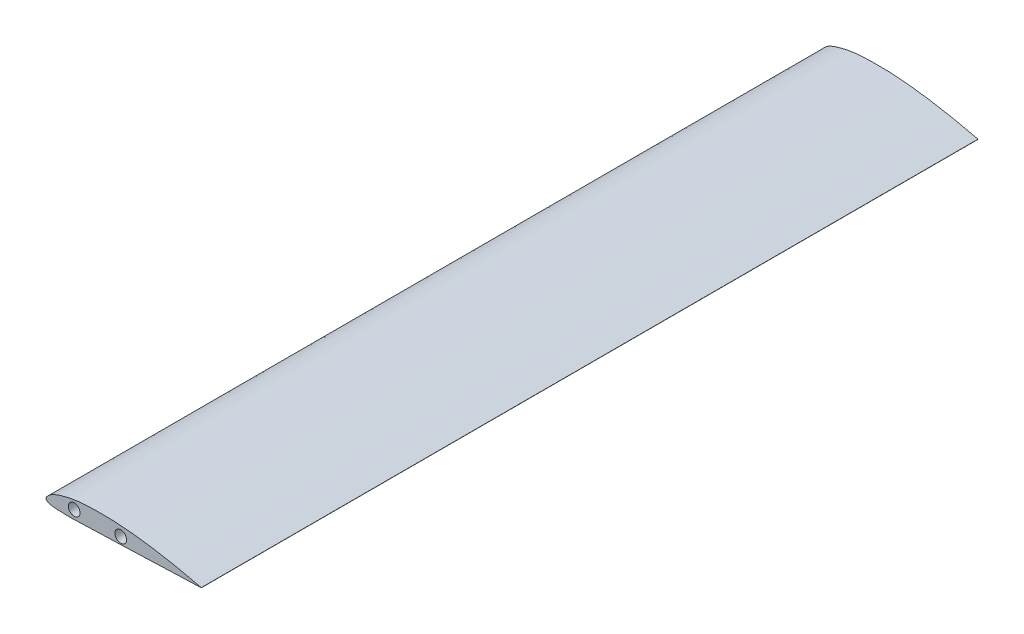
SolidWorks part; units mm, degrees
material "ABS"
ref_plane "Front Plane" through (0, 0, 0) normal (0, 0, 1) x (1, 0, 0)
ref_plane "Top Plane" through (0, 0, 0) normal (0, 1, 0) x (1, 0, 0)
ref_plane "Right Plane" through (0, 0, 0) normal (1, 0, 0) x (0, 0, -1)
curve "Curve1"
  spline degree 3 poles (25.4, 0.0152, 0) (25.3153, 0.0353, 0) (25.146, 0.0754, 0) (24.892, 0.1355, 0) (24.6381, 0.1953, 0) (24.2995, 0.2744, 0) (23.8763, 0.3719, 0) (23.3683, 0.4859, 0) (22.8603, 0.5973, 0) (22.3523, 0.7062, 0) (21.8443, 0.8125, 0) (21.3363, 0.9162, 0) (20.8283, 1.017, 0) (20.3203, 1.1151, 0) (19.8123, 1.2102, 0) (19.3043, 1.3024, 0) (18.7962, 1.3915, 0) (18.2882, 1.4777, 0) (17.7802, 1.5609, 0) (17.2722, 1.6409, 0) (16.7643, 1.7177, 0) (16.2563, 1.7908, 0) (15.7483, 1.8601, 0) (15.2403, 1.9251, 0) (14.7323, 1.9856, 0) (14.2242, 2.0416, 0) (13.7162, 2.093, 0) (13.2082, 2.1398, 0) (12.7002, 2.182, 0) (12.1922, 2.2197, 0) (11.6842, 2.2524, 0) (11.1761, 2.2798, 0) (10.6681, 2.3014, 0) (10.1601, 2.3168, 0) (9.652, 2.3257, 0) (9.144, 2.3283, 0) (8.636, 2.3252, 0) (8.128, 2.3169, 0) (7.6199, 2.3039, 0) (7.1119, 2.2871, 0) (6.6038, 2.2641, 0) (6.0956, 2.2327, 0) (5.5873, 2.1902, 0) (5.079, 2.1342, 0) (4.5707, 2.0617, 0) (4.0625, 1.9727, 0) (3.5542, 1.8677, 0) (3.0455, 1.7457, 0) (2.5366, 1.6033, 0) (2.0278, 1.436, 0) (1.6043, 1.2762, 0) (1.2667, 1.1258, 0) (1.0109, 0.9949, 0) (0.7528, 0.8393, 0) (0.5145, 0.6577, 0) (0.3356, 0.4854, 0) (0.199, 0.3469, 0) (0.1123, 0.2457, 0) (0.0552, 0.1586, 0) (0.0273, 0.1015, 0) (0.0095, 0.0523, 0) (-0.0066, -0.0188, 0) (0.0016, -0.0927, 0) (0.0273, -0.1571, 0) (0.0549, -0.2082, 0) (0.1111, -0.2828, 0) (0.1967, -0.3619, 0) (0.3302, -0.4523, 0) (0.5196, -0.5255, 0) (0.7613, -0.5742, 0) (1.0151, -0.6246, 0) (1.2693, -0.6634, 0) (1.608, -0.6993, 0) (2.0318, -0.7237, 0) (2.5398, -0.7478, 0) (3.0479, -0.7623, 0) (3.556, -0.7692, 0) (4.064, -0.7694, 0) (4.572, -0.764, 0) (5.08, -0.7541, 0) (5.588, -0.7407, 0) (6.096, -0.7247, 0) (6.604, -0.7067, 0) (7.112, -0.6877, 0) (7.62, -0.6682, 0) (8.128, -0.6491, 0) (8.636, -0.6304, 0) (9.144, -0.6118, 0) (9.652, -0.5934, 0) (10.16, -0.5749, 0) (10.668, -0.5564, 0) (11.176, -0.5378, 0) (11.684, -0.519, 0) (12.192, -0.5004, 0) (12.7, -0.4816, 0) (13.208, -0.4629, 0) (13.716, -0.4443, 0) (14.224, -0.4256, 0) (14.732, -0.407, 0) (15.24, -0.3883, 0) (15.748, -0.3697, 0) (16.256, -0.3511, 0) (16.764, -0.3324, 0) (17.272, -0.3137, 0) (17.78, -0.2951, 0) (18.288, -0.2764, 0) (18.796, -0.2578, 0) (19.304, -0.2391, 0) (19.812, -0.2205, 0) (20.32, -0.2018, 0) (20.828, -0.1831, 0) (21.336, -0.1645, 0) (21.844, -0.1458, 0) (22.352, -0.1271, 0) (22.86, -0.1085, 0) (23.368, -0.0898, 0) (23.876, -0.0712, 0) (24.2993, -0.0556, 0) (24.638, -0.0432, 0) (24.892, -0.0339, 0) (25.146, -0.0246, 0) (25.3153, -0.0183, 0) (25.4, -0.0152, 0) knots 0 0 0 0 0.005028 0.010055 0.015081 0.020105 0.030145 0.040174 0.050191 0.060198 0.070194 0.08018 0.090156 0.100121 0.110076 0.12002 0.129954 0.139879 0.149793 0.159699 0.169594 0.17948 0.189355 0.199219 0.209073 0.218917 0.228751 0.238577 0.248396 0.258207 0.268012 0.277811 0.287604 0.297393 0.307179 0.316964 0.326749 0.336535 0.346322 0.356113 0.365908 0.375711 0.385531 0.395376 0.405259 0.415192 0.425184 0.435248 0.445412 0.455711 0.466191 0.471552 0.477055 0.482787 0.488946 0.494316 0.497126 0.500187 0.502001 0.503128 0.50385 0.50502 0.507318 0.507987 0.509024 0.510668 0.513358 0.515716 0.519949 0.524973 0.529954 0.534903 0.539824 0.54963 0.559425 0.569214 0.579 0.588784 0.59857 0.608356 0.618144 0.627933 0.637724 0.647515 0.657307 0.667099 0.67689 0.686681 0.696472 0.706263 0.716054 0.725846 0.735637 0.745428 0.755219 0.765011 0.774802 0.784593 0.794384 0.804176 0.813967 0.823758 0.833549 0.84334 0.853132 0.862923 0.872714 0.882505 0.892297 0.902088 0.911879 0.92167 0.931461 0.941253 0.951044 0.960835 0.970626 0.980418 0.985313 0.990209 0.995104 1 1 1 1
sketch "Sketch1" plane through (0, 0, 0) normal (0, 0, 1) x (1, 0, 0)
  line L1 (50.8, 0.0304) -> (50.8, -0.0304)
  line L2 (0, 0) -> (50.8, -0.0304) construction
  spline S1 degree 3 poles (50.8, 0.0304) (50.6307, 0.0706) (50.292, 0.1509) (49.7841, 0.271) (49.2761, 0.3906) (48.599, 0.5489) (47.7526, 0.7437) (46.7366, 0.9719) (45.7205, 1.1946) (44.7045, 1.4124) (43.6885, 1.625) (42.6725, 1.8324) (41.6565, 2.034) (40.6405, 2.2302) (39.6245, 2.4204) (38.6085, 2.6048) (37.5925, 2.7831) (36.5765, 2.9555) (35.5605, 3.1217) (34.5445, 3.2819) (33.5285, 3.4355) (32.5125, 3.5817) (31.4966, 3.7202) (30.4805, 3.8502) (29.1265, 4.0115) (27.7717, 4.1547) (26.4164, 4.2796) (25.4004, 4.3641) (24.3843, 4.4393) (23.03, 4.5266) (21.6752, 4.5925) (20.3202, 4.6337) (19.3041, 4.6513) (18.288, 4.6566) (17.2719, 4.6503) (16.2559, 4.6338) (15.2399, 4.6078) (14.2238, 4.5741) (13.2075, 4.5283) (12.1912, 4.4655) (11.1747, 4.3804) (10.158, 4.2684) (9.1414, 4.1234) (8.125, 3.9453) (7.1083, 3.7354) (6.091, 3.4914) (5.0732, 3.2065) (4.0556, 2.872) (3.2085, 2.5523) (2.5334, 2.2517) (2.0218, 1.9898) (1.5056, 1.6786) (1.0291, 1.3154) (0.6712, 0.9708) (0.398, 0.6939) (0.2245, 0.4914) (0.1104, 0.3171) (0.0546, 0.2029) (0.019, 0.1046) (-0.0133, -0.0375) (0.0031, -0.1854) (0.0546, -0.3141) (0.1099, -0.4165) (0.2221, -0.5657) (0.3933, -0.7238) (0.6603, -0.9046) (1.0392, -1.0509) (1.5225, -1.1483) (2.0302, -1.2493) (2.5386, -1.3268) (3.216, -1.3987) (4.0636, -1.4474) (5.0796, -1.4956) (6.0958, -1.5247) (7.112, -1.5384) (8.128, -1.5388) (9.1441, -1.528) (10.4989, -1.5016) (11.8535, -1.4613) (13.208, -1.4134) (14.224, -1.3753) (15.24, -1.3363) (16.256, -1.2981) (17.272, -1.2607) (18.288, -1.2236) (19.304, -1.1868) (20.32, -1.1498) (21.336, -1.1127) (22.352, -1.0755) (23.368, -1.0381) (24.384, -1.0007) (25.4, -0.9633) (26.416, -0.9259) (27.432, -0.8885) (29.1253, -0.8264) (30.8187, -0.7642) (32.8507, -0.6897) (34.2053, -0.6398) (35.56, -0.5902) (36.576, -0.5528) (37.592, -0.5155) (38.608, -0.4782) (39.624, -0.4409) (40.64, -0.4035) (41.656, -0.3663) (42.672, -0.3289) (43.688, -0.2917) (44.704, -0.2543) (45.72, -0.217) (46.736, -0.1797) (47.752, -0.1424) (48.5987, -0.1113) (49.276, -0.0864) (49.784, -0.0678) (50.292, -0.0491) (50.6307, -0.0367) (50.8, -0.0304) knots 0 0 0 0 0.005028 0.010055 0.015081 0.020105 0.030145 0.040174 0.050191 0.060198 0.070194 0.08018 0.090156 0.100121 0.110076 0.12002 0.129954 0.139879 0.149793 0.159699 0.169594 0.17948 0.189355 0.199219 0.209073 0.228751 0.238577 0.248396 0.258207 0.268012 0.287604 0.297393 0.307179 0.316964 0.326749 0.336535 0.346322 0.356113 0.365908 0.375711 0.385531 0.395376 0.405259 0.415192 0.425184 0.435248 0.445412 0.455711 0.466191 0.471552 0.477055 0.482787 0.488946 0.494316 0.497126 0.500187 0.502001 0.503128 0.50385 0.50502 0.507318 0.507987 0.509024 0.510668 0.513358 0.515716 0.519949 0.524973 0.529954 0.534903 0.539824 0.54963 0.559425 0.569214 0.579 0.588784 0.59857 0.608356 0.627933 0.637724 0.647515 0.657307 0.667099 0.67689 0.686681 0.696472 0.706263 0.716054 0.725846 0.735637 0.745428 0.755219 0.765011 0.774802 0.784593 0.813967 0.823758 0.84334 0.853132 0.862923 0.872714 0.882505 0.892297 0.902088 0.911879 0.92167 0.931461 0.941253 0.951044 0.960835 0.970626 0.980418 0.985313 0.990209 0.995104 1 1 1 1
  dimension "D1" = 50.8
extrude "Boss-Extrude1" add sketch "Sketch1" along normal blind 254
sketch "Sketch2" plane through (0, 0, 254) normal (0, 0, 1) x (1, 0, 0)
  circle A0 centre (9.2203, 1.3354) radius 1.905
  circle A1 centre (24.4603, 1.3354) radius 1.905
  point P4 (6.3193, 1.1662)
  point P5 (8.5917, 1.5288)
  point P6 (9.2203, 1.3354)
  dimension "D1" = 3.81
  dimension "D3" = 3.81
  dimension "D2" = 15.24
extrude "Cut-Extrude1" cut sketch "Sketch2" against normal blind 12.7
